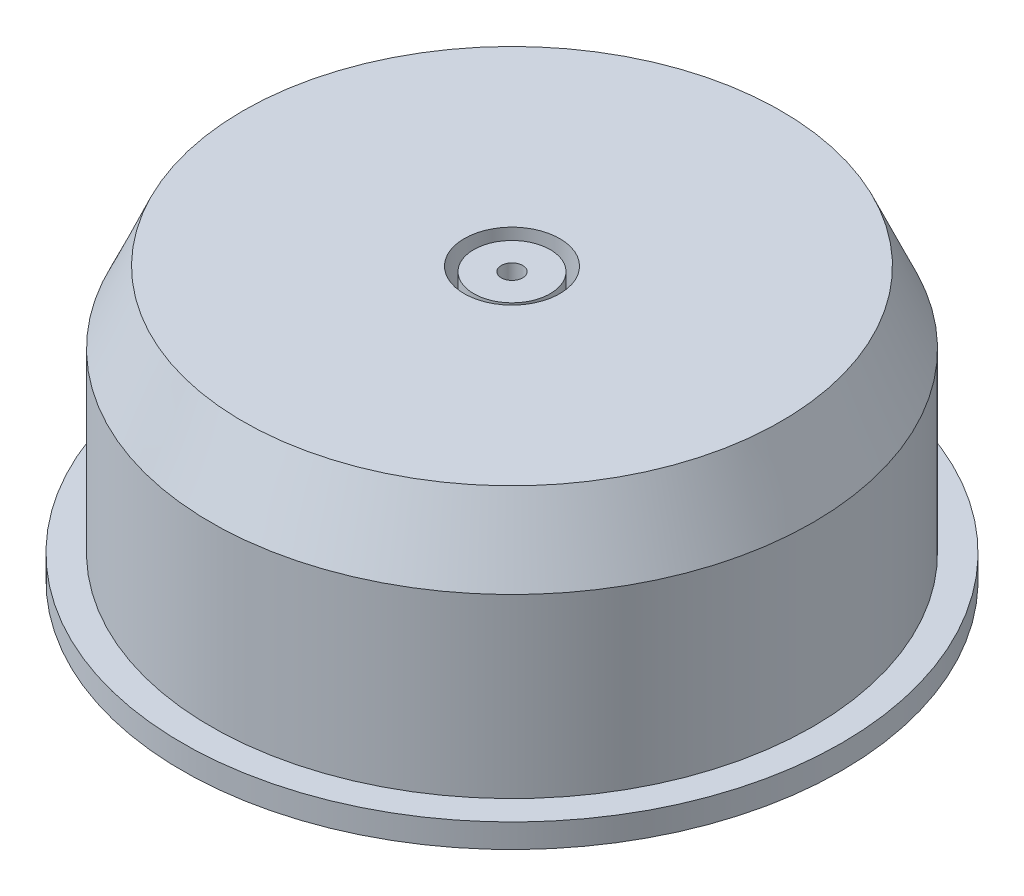
SolidWorks part; units mm, degrees
material "Д16Т ГОСТ 4784-97"
ref_plane "Спереди" through (0, 0, 0) normal (0, 0, 1) x (1, 0, 0)
ref_plane "Сверху" through (0, 0, 0) normal (0, 1, 0) x (1, 0, 0)
ref_plane "Справа" through (0, 0, 0) normal (1, 0, 0) x (0, 0, -1)
other "Configuration Table"
sketch "Эскиз2" plane through (0, 0, 0) normal (0, 0, 1) x (1, 0, 0)
  line L0 (-10, -1.9782) -> (-56.3333, -1.9782)
  line L1 (-56.3333, -1.9782) -> (-63, -16.9782)
  line L5 (-63, -16.9782) -> (-63, -53.9782)
  line L6 (-63, -53.9782) -> (-69, -53.9782)
  line L7 (-69, -53.9782) -> (-69, -58.9782)
  line L8 (-69, -58.9782) -> (-34.2989, -58.9782)
  line L9 (-34.2989, -58.9782) -> (-25.2989, -62.9782)
  line L10 (-25.2989, -62.9782) -> (0, -62.9782)
  line L11 (0, -2.9782) -> (0, -70.5392) construction
  line L12 (0, -2.9782) -> (0, -62.9782)
  line L13 (-8, -13.7306) -> (-8, -2.9782)
  line L14 (0, -2.9782) -> (-8, -2.9782)
  line L15 (-8, -13.7306) -> (-10, -13.7306)
  line L16 (-10, -13.7306) -> (-10, -1.9782)
  dimension "D2" = 63
  dimension "D3" = 15
  dimension "D6" = 37
  dimension "D7" = 5
  dimension "D9" = 4
  dimension "D11" = 6
  dimension "D12" = 8
  dimension "60" = 60
revolve "Повернуть1" add sketch "Эскиз2" angle 360 about L11
sketch "Эскиз3" plane through (0, -62.9782, 0) normal (0, -1, 0) x (1, 0, 0)
  circle A0 centre (0, 0) radius 8
extrude "Бобышка-Вытянуть1" add sketch "Эскиз3" along normal blind 27
sketch "Эскиз4" plane through (0, -89.9782, 0) normal (0, -1, 0) x (1, 0, 0)
  line L1 (-11.0002, 11.8096) -> (10.8692, 11.8096)
  line L2 (-11.0002, 11.8096) -> (-11.0002, 5)
  line L3 (-11.0002, 5) -> (10.8692, 5)
  line L4 (10.8692, 11.8096) -> (10.8692, 5)
  dimension "D1" = 5
extrude "Вырез-Вытянуть1" cut sketch "Эскиз4" against normal blind 23
sketch "Эскиз5" plane through (0, -89.9782, 0) normal (0, -1, 0) x (1, 0, 0)
  circle A0 centre (0, 0) radius 3.5
  dimension "D1" = 7
extrude "Вырез-Вытянуть2" cut sketch "Эскиз5" against normal blind 70
hole_wizard "Зенковка для винта с полупотайной головкой M51" positions "Эскиз6" profile "Эскиз7" countersink size "M5" standard "ISO"
sketch "Эскиз6" plane through (0, -58.9782, 0) normal (0, -1, 0) x (-1, 0, 0)
  point P0 (1.1577, 60)
  dimension "D1" = 60
sketch "Эскиз7" plane through (-1.1577, -58.9782, -60) normal (1, 0, 0) x (0, 0, -1)
  line L0 (0, 0) -> (0, 15.6524)
  line L1 (0, 15.6524) -> (2.75, 14)
  line L2 (2.75, 14) -> (2.75, 2.45)
  line L3 (2.75, 2.45) -> (5.2, 0)
  line L5 (5.2, 0) -> (0, 0)
  line L6 (-2.75, 2.45) -> (-5.2, 0) construction
  line L10 (0, 15.6524) -> (-2.75, 14) construction
  line L11 (0, -6.35) -> (0, 107.95) construction
  dimension "Диаметр отверстия" = 5.5
  dimension "Глубина отверстия" = 14
  dimension "Диаметр передней зенковки" = 10.4
  dimension "Угол передней зенковки" = 90
  dimension "Угол заточки сверла" = 118
pattern_circular "Круговой массив1" count 6 over 360 about axis through (0, 0, 0) along (0, 1, 0) of "Зенковка для винта с полупотайной головкой M51"
sketch "Эскиз8" plane through (0, -1.9782, 0) normal (0, 1, 0) x (1, 0, 0)
  circle A0 centre (0, 0) radius 6
  dimension "D1" = 12
extrude "Вырез-Вытянуть3" [suppressed] cut sketch "Эскиз8" against normal blind 6
sketch "Эскиз9" [suppressed] plane through (0, -6, 0) normal (0, 1, 0) x (1, 0, 0)
  circle A0 centre (0, 0) radius 2.5
  dimension "D1" = 5
extrude "Бобышка-Вытянуть2" [suppressed] add sketch "Эскиз9" along normal blind 12
sketch "Эскиз10" [suppressed] plane through (0, 6, 0) normal (0, 1, 0) x (1, 0, 0)
  circle A0 centre (0, 0) radius 4.5
  dimension "D1" = 9
extrude "Бобышка-Вытянуть3" [suppressed] add sketch "Эскиз10" along normal blind 5
sketch "Эскиз11" [suppressed] plane through (0, 11, 0) normal (0, 1, 0) x (1, 0, 0)
  circle A0 centre (0, 0) radius 2.65
  dimension "D1" = 5.3
extrude "Вырез-Вытянуть4" [suppressed] cut sketch "Эскиз11" against normal blind 3 contours A0
chamfer "Фаска1" [suppressed] distance 1 angle 45
hole_wizard "Отверстие с зазором M41" positions "Эскиз13" profile "Эскиз12" hole size "M4" standard "ISO"
sketch "Эскиз13" plane through (0, -2.9782, 0) normal (0, 1, 0) x (1, 0, 0)
  point P0 (0, 0)
sketch "Эскиз12" plane through (0, -2.9782, 0) normal (1, 0, 0) x (0, 0, 1)
  line L0 (0, 0) -> (0, 15.3519)
  line L1 (0, 15.3519) -> (2.25, 14)
  line L2 (2.25, 14) -> (2.25, 0)
  line L5 (2.25, 0) -> (0, 0)
  line L10 (0, 15.3519) -> (-2.25, 14) construction
  line L11 (0, -6.35) -> (0, 107.95) construction
  dimension "Диаметр отверстия" = 4.5
  dimension "Глубина отверстия" = 14
  dimension "Угол заточки сверла" = 118
sketch "Эскиз14" plane through (0, -62.9782, 0) normal (0, -1, 0) x (1, 0, 0)
  circle A0 centre (0, 0) radius 8
  circle A1 centre (0, 0) radius 9.9506
extrude "Вырез-Вытянуть5" cut sketch "Эскиз14" against normal blind 10
